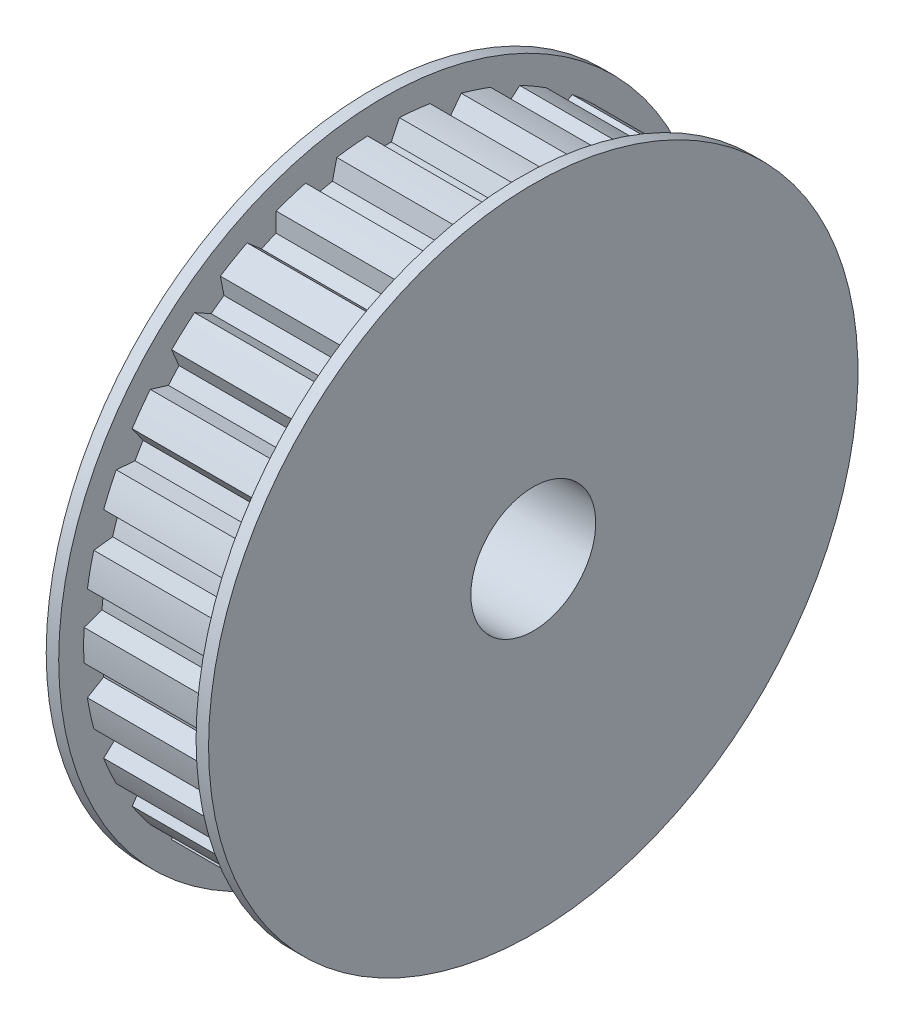
SolidWorks part; units mm, degrees
ref_plane "Front Plane" through (0, 0, 0) normal (0, 0, 1) x (1, 0, 0)
ref_plane "Top Plane" through (0, 0, 0) normal (0, 1, 0) x (1, 0, 0)
ref_plane "Right Plane" through (0, 0, 0) normal (1, 0, 0) x (0, 0, -1)
sketch "Sketch1" plane through (0, 0, 0) normal (1, 0, 0) x (0, 0, -1)
  line L0 (0, 24) -> (0, 0) construction
  circle A0 centre (0, 0) radius 24
  circle A1 centre (0, 0) radius 5
  dimension "D1" = 48
  dimension "D2" = 10
extrude "Boss-Extrude1" add sketch "Sketch1" along normal blind 11
sketch "Sketch2" plane through (0, 0, 0) normal (-1, 0, 0) x (0, 0, 1)
  line L0 (0, 0) -> (0, 24) construction
  line L1 (1.2761, 23.9661) -> (0.6349, 22.5911)
  line L2 (-1.2761, 23.9661) -> (-0.6349, 22.5911)
  line L3 (6.231, 23.177) -> (5.318, 21.9654)
  line L4 (3.7346, 23.7076) -> (4.0759, 22.2294)
  line L5 (10.9136, 21.3751) -> (9.7686, 20.3797)
  line L6 (8.5821, 22.4131) -> (8.6086, 20.8962)
  line L7 (15.1193, 18.6389) -> (13.7924, 17.9034)
  line L8 (13.0545, 20.139) -> (12.765, 18.6498)
  line L9 (18.6641, 15.0881) -> (17.2133, 14.6445)
  line L10 (16.9564, 16.9847) -> (16.3636, 15.5882)
  line L11 (21.3932, 10.8779) -> (19.8819, 10.7457)
  line L12 (20.1172, 13.0881) -> (19.247, 11.8454)
  line L13 (23.1874, 6.1923) -> (21.6816, 6.3772)
  line L14 (22.3987, 8.6195) -> (21.2892, 7.5849)
  line L15 (23.9681, 1.236) -> (22.5337, 1.73)
  line L16 (23.7014, 3.7742) -> (22.401, 2.9928)
  line L17 (23.7014, -3.7742) -> (22.401, -2.9928)
  line L18 (23.9681, -1.236) -> (22.5337, -1.73)
  line L19 (22.3987, -8.6195) -> (21.2892, -7.5849)
  line L20 (23.1874, -6.1923) -> (21.6816, -6.3772)
  line L21 (20.1172, -13.0881) -> (19.247, -11.8454)
  line L22 (21.3932, -10.8779) -> (19.8819, -10.7457)
  line L23 (16.9564, -16.9847) -> (16.3636, -15.5882)
  line L24 (18.6641, -15.0881) -> (17.2133, -14.6445)
  line L25 (13.0545, -20.139) -> (12.765, -18.6498)
  line L26 (15.1193, -18.6389) -> (13.7924, -17.9034)
  line L27 (8.5821, -22.4131) -> (8.6086, -20.8962)
  line L28 (10.9136, -21.3751) -> (9.7686, -20.3797)
  line L29 (3.7346, -23.7076) -> (4.0759, -22.2294)
  line L30 (6.231, -23.177) -> (5.318, -21.9654)
  line L31 (-1.2761, -23.9661) -> (-0.6349, -22.5911)
  line L32 (1.2761, -23.9661) -> (0.6349, -22.5911)
  line L33 (-6.231, -23.177) -> (-5.318, -21.9654)
  line L34 (-3.7346, -23.7076) -> (-4.0759, -22.2294)
  line L35 (-10.9136, -21.3751) -> (-9.7686, -20.3797)
  line L36 (-8.5821, -22.4131) -> (-8.6086, -20.8962)
  line L37 (-15.1193, -18.6389) -> (-13.7924, -17.9034)
  line L38 (-13.0545, -20.139) -> (-12.765, -18.6498)
  line L39 (-18.6641, -15.0881) -> (-17.2133, -14.6445)
  line L40 (-16.9564, -16.9847) -> (-16.3636, -15.5882)
  line L41 (-21.3932, -10.8779) -> (-19.8819, -10.7457)
  line L42 (-20.1172, -13.0881) -> (-19.247, -11.8454)
  line L43 (-23.1874, -6.1923) -> (-21.6816, -6.3772)
  line L44 (-22.3987, -8.6195) -> (-21.2892, -7.5849)
  line L45 (-23.9681, -1.236) -> (-22.5337, -1.73)
  line L46 (-23.7014, -3.7742) -> (-22.401, -2.9928)
  line L47 (-23.7014, 3.7742) -> (-22.401, 2.9928)
  line L48 (-23.9681, 1.236) -> (-22.5337, 1.73)
  line L49 (-22.3987, 8.6195) -> (-21.2892, 7.5849)
  line L50 (-23.1874, 6.1923) -> (-21.6816, 6.3772)
  line L51 (-20.1172, 13.0881) -> (-19.247, 11.8454)
  line L52 (-21.3932, 10.8779) -> (-19.8819, 10.7457)
  line L53 (-16.9564, 16.9847) -> (-16.3636, 15.5882)
  line L54 (-18.6641, 15.0881) -> (-17.2133, 14.6445)
  line L55 (-13.0545, 20.139) -> (-12.765, 18.6498)
  line L56 (-15.1193, 18.6389) -> (-13.7924, 17.9034)
  line L57 (-8.5821, 22.4131) -> (-8.6086, 20.8962)
  line L58 (-10.9136, 21.3751) -> (-9.7686, 20.3797)
  line L59 (-3.7346, 23.7076) -> (-4.0759, 22.2294)
  line L60 (-6.231, 23.177) -> (-5.318, 21.9654)
  circle A0 centre (0, 0) radius 24 construction
  arc A1 (1.2761, 23.9661) -> (-1.2761, 23.9661) centre (0, 0) ccw
  arc A2 (0.6349, 22.5911) -> (-0.6349, 22.5911) centre (0, 0) ccw
  arc A3 (6.231, 23.177) -> (3.7346, 23.7076) centre (0, 0) ccw
  arc A4 (5.318, 21.9654) -> (4.0759, 22.2294) centre (0, 0) ccw
  arc A5 (10.9136, 21.3751) -> (8.5821, 22.4131) centre (0, 0) ccw
  arc A6 (9.7686, 20.3797) -> (8.6086, 20.8962) centre (0, 0) ccw
  arc A7 (15.1193, 18.6389) -> (13.0545, 20.139) centre (0, 0) ccw
  arc A8 (13.7924, 17.9034) -> (12.765, 18.6498) centre (0, 0) ccw
  arc A9 (18.6641, 15.0881) -> (16.9564, 16.9847) centre (0, 0) ccw
  arc A10 (17.2133, 14.6445) -> (16.3636, 15.5882) centre (0, 0) ccw
  arc A11 (21.3932, 10.8779) -> (20.1172, 13.0881) centre (0, 0) ccw
  arc A12 (19.8819, 10.7457) -> (19.247, 11.8454) centre (0, 0) ccw
  arc A13 (23.1874, 6.1923) -> (22.3987, 8.6195) centre (0, 0) ccw
  arc A14 (21.6816, 6.3772) -> (21.2892, 7.5849) centre (0, 0) ccw
  arc A15 (23.9681, 1.236) -> (23.7014, 3.7742) centre (0, 0) ccw
  arc A16 (22.5337, 1.73) -> (22.401, 2.9928) centre (0, 0) ccw
  arc A17 (23.7014, -3.7742) -> (23.9681, -1.236) centre (0, 0) ccw
  arc A18 (22.401, -2.9928) -> (22.5337, -1.73) centre (0, 0) ccw
  arc A19 (22.3987, -8.6195) -> (23.1874, -6.1923) centre (0, 0) ccw
  arc A20 (21.2892, -7.5849) -> (21.6816, -6.3772) centre (0, 0) ccw
  arc A21 (20.1172, -13.0881) -> (21.3932, -10.8779) centre (0, 0) ccw
  arc A22 (19.247, -11.8454) -> (19.8819, -10.7457) centre (0, 0) ccw
  arc A23 (16.9564, -16.9847) -> (18.6641, -15.0881) centre (0, 0) ccw
  arc A24 (16.3636, -15.5882) -> (17.2133, -14.6445) centre (0, 0) ccw
  arc A25 (13.0545, -20.139) -> (15.1193, -18.6389) centre (0, 0) ccw
  arc A26 (12.765, -18.6498) -> (13.7924, -17.9034) centre (0, 0) ccw
  arc A27 (8.5821, -22.4131) -> (10.9136, -21.3751) centre (0, 0) ccw
  arc A28 (8.6086, -20.8962) -> (9.7686, -20.3797) centre (0, 0) ccw
  arc A29 (3.7346, -23.7076) -> (6.231, -23.177) centre (0, 0) ccw
  arc A30 (4.0759, -22.2294) -> (5.318, -21.9654) centre (0, 0) ccw
  arc A31 (-1.2761, -23.9661) -> (1.2761, -23.9661) centre (0, 0) ccw
  arc A32 (-0.6349, -22.5911) -> (0.6349, -22.5911) centre (0, 0) ccw
  arc A33 (-6.231, -23.177) -> (-3.7346, -23.7076) centre (0, 0) ccw
  arc A34 (-5.318, -21.9654) -> (-4.0759, -22.2294) centre (0, 0) ccw
  arc A35 (-10.9136, -21.3751) -> (-8.5821, -22.4131) centre (0, 0) ccw
  arc A36 (-9.7686, -20.3797) -> (-8.6086, -20.8962) centre (0, 0) ccw
  arc A37 (-15.1193, -18.6389) -> (-13.0545, -20.139) centre (0, 0) ccw
  arc A38 (-13.7924, -17.9034) -> (-12.765, -18.6498) centre (0, 0) ccw
  arc A39 (-18.6641, -15.0881) -> (-16.9564, -16.9847) centre (0, 0) ccw
  arc A40 (-17.2133, -14.6445) -> (-16.3636, -15.5882) centre (0, 0) ccw
  arc A41 (-21.3932, -10.8779) -> (-20.1172, -13.0881) centre (0, 0) ccw
  arc A42 (-19.8819, -10.7457) -> (-19.247, -11.8454) centre (0, 0) ccw
  arc A43 (-23.1874, -6.1923) -> (-22.3987, -8.6195) centre (0, 0) ccw
  arc A44 (-21.6816, -6.3772) -> (-21.2892, -7.5849) centre (0, 0) ccw
  arc A45 (-23.9681, -1.236) -> (-23.7014, -3.7742) centre (0, 0) ccw
  arc A46 (-22.5337, -1.73) -> (-22.401, -2.9928) centre (0, 0) ccw
  arc A47 (-23.7014, 3.7742) -> (-23.9681, 1.236) centre (0, 0) ccw
  arc A48 (-22.401, 2.9928) -> (-22.5337, 1.73) centre (0, 0) ccw
  arc A49 (-22.3987, 8.6195) -> (-23.1874, 6.1923) centre (0, 0) ccw
  arc A50 (-21.2892, 7.5849) -> (-21.6816, 6.3772) centre (0, 0) ccw
  arc A51 (-20.1172, 13.0881) -> (-21.3932, 10.8779) centre (0, 0) ccw
  arc A52 (-19.247, 11.8454) -> (-19.8819, 10.7457) centre (0, 0) ccw
  arc A53 (-16.9564, 16.9847) -> (-18.6641, 15.0881) centre (0, 0) ccw
  arc A54 (-16.3636, 15.5882) -> (-17.2133, 14.6445) centre (0, 0) ccw
  arc A55 (-13.0545, 20.139) -> (-15.1193, 18.6389) centre (0, 0) ccw
  arc A56 (-12.765, 18.6498) -> (-13.7924, 17.9034) centre (0, 0) ccw
  arc A57 (-8.5821, 22.4131) -> (-10.9136, 21.3751) centre (0, 0) ccw
  arc A58 (-8.6086, 20.8962) -> (-9.7686, 20.3797) centre (0, 0) ccw
  arc A59 (-3.7346, 23.7076) -> (-6.231, 23.177) centre (0, 0) ccw
  arc A60 (-4.0759, 22.2294) -> (-5.318, 21.9654) centre (0, 0) ccw
  point P10 (0, 22.6)
  point P18 (4.6988, 22.1061)
  point P23 (9.1922, 20.6461)
  point P28 (13.2839, 18.2838)
  point P33 (16.7951, 15.1224)
  point P38 (19.5722, 11.3)
  point P43 (21.4939, 6.9838)
  point P48 (22.4762, 2.3623)
  point P53 (22.4762, -2.3623)
  point P58 (21.4939, -6.9838)
  point P63 (19.5722, -11.3)
  point P68 (16.7951, -15.1224)
  point P73 (13.2839, -18.2838)
  point P78 (9.1922, -20.6461)
  point P83 (4.6988, -22.1061)
  point P88 (0, -22.6)
  point P93 (-4.6988, -22.1061)
  point P98 (-9.1922, -20.6461)
  point P103 (-13.2839, -18.2838)
  point P108 (-16.7951, -15.1224)
  point P113 (-19.5722, -11.3)
  point P118 (-21.4939, -6.9838)
  point P123 (-22.4762, -2.3623)
  point P128 (-22.4762, 2.3623)
  point P133 (-21.4939, 6.9838)
  point P138 (-19.5722, 11.3)
  point P143 (-16.7951, 15.1224)
  point P148 (-13.2839, 18.2838)
  point P153 (-9.1922, 20.6461)
  point P158 (-4.6988, 22.1061)
  point P159 (0, 0)
  dimension "D1" = 1.4
  dimension "D2" = 25
  dimension "D3" = 0.635
  dimension "D4" = 30
extrude "Cut-Extrude1" cut sketch "Sketch2" against normal through all
sketch "Sketch3" plane through (0, 0, 0) normal (-1, 0, 0) x (0, 0, 1)
  circle A0 centre (0, 0) radius 26
  circle A1 centre (0, 0) radius 5
  arc A2 (3.7346, 23.7076) -> (1.2761, 23.9661) centre (0, 0) ccw construction
  circle A3 centre (0, 0) radius 5 construction
  dimension "D1" = 2
extrude "Boss-Extrude2" add sketch "Sketch3" along normal blind 1
pattern_linear "LPattern1" count 2 spacing 12 along (1, 0, 0) of "Boss-Extrude2"
